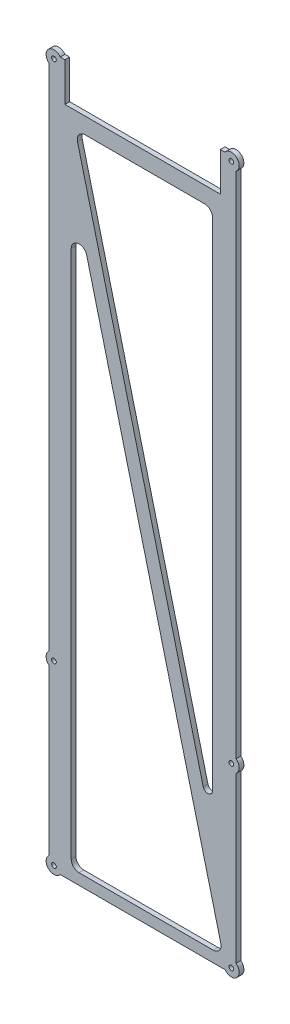
SolidWorks part; units mm, degrees
ref_plane "前视基准面" through (0, 0, 0) normal (0, 0, 1) x (1, 0, 0)
ref_plane "上视基准面" through (0, 0, 0) normal (0, 1, 0) x (1, 0, 0)
ref_plane "右视基准面" through (0, 0, 0) normal (1, 0, 0) x (0, 0, -1)
sketch "草图1" plane through (0, 0, 0) normal (0, 0, 1) x (1, 0, 0)
  line L0 (0, 0) -> (113, 0) construction
  line L3 (0, -445) -> (0, 0) construction
  line L4 (-3, 3) -> (116, 3) construction
  line L5 (116, 3) -> (116, -448) construction
  line L6 (116, -448) -> (-3, -448) construction
  line L7 (-3, -448) -> (-3, 3) construction
  line L8 (0, -445) -> (0, -332.18) construction
  line L9 (116, -441) -> (116, -336.18)
  line L10 (116, -328.18) -> (116, -4)
  line L11 (109, 3) -> (4, 3) construction
  line L12 (-3, -4) -> (-3, -328.18)
  line L13 (-3, -336.18) -> (-3, -441)
  line L14 (4, -448) -> (109, -448)
  line L15 (7, -27) -> (7, 3) construction
  line L16 (7, -27) -> (106, -27) construction
  line L17 (106, -27) -> (106, 3) construction
  line L18 (106, 3) -> (109, 3)
  line L19 (7, 3) -> (4, 3)
  line L20 (7, -27) -> (113, -445) construction
  line L21 (106, -27) -> (106, -417.3962) construction
  line L22 (7, -445) -> (113, -445) construction
  line L23 (101, -37) -> (101, -353.3033)
  line L24 (20.8466, -97.8755) -> (106.2794, -434.771)
  line L25 (16, -441) -> (101.4328, -441)
  line L26 (11, -436) -> (11, -99.1045)
  line L27 (106, -417.3962) -> (7, -27) construction
  line L28 (95.092, -354.0408) -> (15.0058, -38.229)
  line L29 (7, -445) -> (7, -27) construction
  line L30 (19.8524, -32) -> (96, -32)
  line L31 (7, -21.6458) -> (106, -21.6458)
  line L32 (7, 3) -> (7, -21.6458)
  line L33 (106, -21.6458) -> (106, 3)
  line L34 (101, -32) -> (101, -377.3382) construction
  line L35 (13.4262, -32) -> (101, -32) construction
  line L36 (101, -377.3382) -> (13.4262, -32) construction
  line L37 (11, -59.0464) -> (107.859, -441) construction
  line L38 (11, -441) -> (107.859, -441) construction
  line L39 (11, -441) -> (11, -59.0464) construction
  circle A0 centre (0, 0) radius 1.5
  circle A1 centre (113, 0) radius 1.5
  circle A2 centre (113, -445) radius 1.5
  circle A3 centre (0, -445) radius 1.5
  circle A4 centre (0, -332.18) radius 1.5
  circle A5 centre (113, -332.18) radius 1.5
  circle A6 centre (0, 0) radius 5 construction
  circle A7 centre (113, 0) radius 5 construction
  circle A8 centre (113, -445) radius 5 construction
  circle A9 centre (0, -445) radius 5 construction
  circle A10 centre (113, -332.18) radius 5 construction
  circle A11 centre (0, -332.18) radius 5 construction
  arc A12 (4, -448) -> (-3, -441) centre (0, -445) cw
  arc A13 (109, -448) -> (116, -441) centre (113, -445) ccw
  arc A14 (116, -336.18) -> (116, -328.18) centre (113, -332.18) ccw
  arc A15 (109, 3) -> (116, -4) centre (113, 0) cw
  arc A16 (4, 3) -> (-3, -4) centre (0, 0) ccw
  arc A17 (-3, -336.18) -> (-3, -328.18) centre (0, -332.18) cw
  arc A18 (101, -37) -> (96, -32) centre (96, -37) ccw
  arc A19 (15.0058, -38.229) -> (19.8524, -32) centre (19.8524, -37) cw
  arc A20 (106.2794, -434.771) -> (101.4328, -441) centre (101.4328, -436) cw
  arc A21 (16, -441) -> (11, -436) centre (16, -436) cw
  arc A22 (11, -99.1045) -> (20.8466, -97.8755) centre (16, -99.1045) cw
  arc A23 (101, -353.3033) -> (95.092, -354.0408) centre (98, -353.3033) cw
  dimension "D1" = 5
  dimension "D7" = 10
  dimension "D2" = 3
  dimension "D4" = 3
  dimension "D6" = 3
  dimension "D8" = 10
  dimension "D9" = 30
extrude "凸台-拉伸1" add sketch "草图1" along normal blind 3
